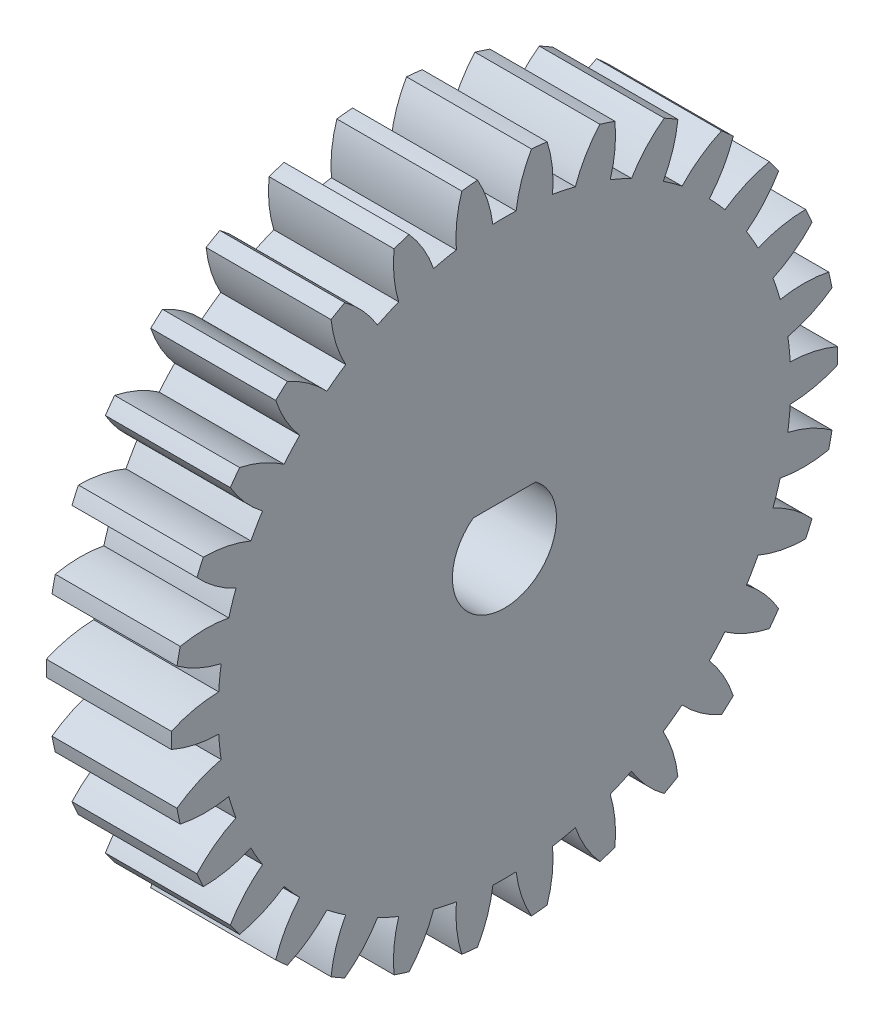
SolidWorks part; units mm, degrees
material "ABS"
ref_plane "Plane1" through (0, 0, 0) normal (0, 0, 1) x (1, 0, 0)
ref_plane "Plane2" through (0, 0, 0) normal (0, 1, 0) x (1, 0, 0)
ref_plane "Plane3" through (0, 0, 0) normal (1, 0, 0) x (0, 0, -1)
other "Configuration Table"
sketch "HoldingSke" plane through (0, 0, 0) normal (0, 1, 0) x (1, 0, 0)
  line L0 (0, 0) -> (0.866, -0.5)
  line L1 (-15, 0) -> (100, 0) construction
  line L2 (0, 0) -> (-2.1039, 2.3779)
  line L3 (0, 0) -> (-11.863, 4.5341)
  line L4 (0, 0) -> (7.479, 4.318)
  line L5 (0, 0) -> (-46.8476, -17.4728)
  line L6 (0, 0) -> (-4.9738, -3.3558)
  line L7 (-2.1039, 2.3779) -> (8.6586, 51.2059)
  line L8 (-76.2, 54.61) -> (-72.9, 54.61)
  line L9 (-67.7845, 28.3722) -> (-49.3413, 33.142)
  line L10 (-76.2, 71.12) -> (104.1128, 71.12)
  line L11 (0, 0) -> (-6, 0)
  line L12 (-76.2, 101.6) -> (-76.162, 101.6)
  line L13 (24.9733, 27.94) -> (52.9518, 28.4284)
  line L14 (24.9733, 27.94) -> (24.9743, 27.94)
  line L15 (24.9733, 27.94) -> (100.4006, 29.5858)
  line L16 (-63.627, -1) -> (-12.827, -1)
  circle A0 centre (0, 0) radius 13
  circle A1 centre (0, 0) radius 13.749
  circle A2 centre (0, 0) radius 37.5
  circle A3 centre (0, 0) radius 13
  dimension "MHD" = 27.498
  dimension "Hub_dia" = 75
  dimension "Bore" = 26
  dimension "MBD" = 26
  dimension "Num_teeth" = 30
  dimension "Pitch" = 1
  dimension "Overall_len" = 50
  dimension "Show_teeth" = 30
  dimension "Thickness" = 6
  dimension "OAL" = 50.0001
  dimension "T_dim" = 3.3
  dimension "Ap" = 14.5
  dimension "H" = 19.05
  dimension "Pitch_radius" = 180.3128
  dimension "Width" = 6
  dimension "Backlash" = 0.038
  dimension "Addendum_fac" = 1
  dimension "Dedendum_fac" = 1.25
  dimension "Clearance_fac" = 0.25
  dimension "Dedendum_add" = 0.001
  dimension "Module" = 1
sketch "BasProSke" plane through (0, 0, 0) normal (0, 1, 0) x (1, 0, 0)
  line L0 (-10, 0) -> (60, 0) construction
  line L1 (0, 0) -> (0, 16)
  line L2 (0, 0) -> (6, 0)
  line L3 (6, 0) -> (6, 16)
  line L4 (6, 16) -> (0, 16)
  dimension "Thickness" = 6
  dimension "Diameter" = 32
revolve "Base-Revolve" add sketch "BasProSke" angle 360 about L0
sketch "TooCutSke" plane through (0, 0, 0) normal (1, 0, 0) x (0, 0, -1)
  line L1 (0, 0) -> (0, 107) construction
  line L2 (0, 0) -> (-0.8515, 14.9758) construction
  line L3 (0, 0) -> (-3.1323, 29.8014) construction
  line L4 (-0.8515, 14.9758) -> (-1.5661, 14.9007) construction
  arc A0 (0.5582, 13.7377) -> (-0.5582, 13.7377) centre (0, 0) ccw
  arc A1 (1.3088, 15.9719) -> (-1.3088, 15.9719) centre (0, 0) ccw
  circle A2 centre (0, 0) radius 15 construction
  circle A3 centre (0, 0) radius 14.5222 construction
  arc A4 (-0.5582, 13.7377) -> (-1.3088, 15.9719) centre (-6.5103, 12.9812) ccw
  arc A5 (1.3088, 15.9719) -> (0.5582, 13.7377) centre (6.5103, 12.9812) ccw
  dimension "Root_dia" = 27.498
  dimension "Overcut_dia" = 32.0508
  dimension "Pitch_dia" = 30
  dimension "Base_dia" = 29.0444
  dimension "Flank_rad" = 6
  dimension "Half_ang" = 6
  dimension "Half_CT" = 0.7185
extrude "ToothCut" cut sketch "TooCutSke" along normal through all
fillet "Breaks" [suppressed] radius 0.02
fillet "RootFillets" [suppressed] radius 0.251
pattern_circular "TeethCuts" count 30 every 12 about axis through (-10, 0, 0) along (1, 0, 0) of "ToothCut", "RootFillets", "Breaks"
sketch "HubNeaOneSke" plane through (0, 0, 0) normal (-1, 0, 0) x (0, 0, 1)
  circle A0 centre (0, 0) radius 13.749
  dimension "Diameter" = 27.498
extrude "HubNearOne" [suppressed] add sketch "HubNeaOneSke" along normal blind 44.0001
sketch "HubNeaBotSke" plane through (0, 0, 0) normal (-1, 0, 0) x (0, 0, 1)
  circle A0 centre (0, 0) radius 13.749
  dimension "Diameter" = 27.498
extrude "HubNearBoth" [suppressed] add sketch "HubNeaBotSke" along normal blind 22
ref_plane "FarPln" through (6, 0, 0) normal (1, 0, 0) x (0, 0, -1)
sketch "HubFarSke" plane through (6, 0, 0) normal (1, 0, 0) x (0, 0, -1)
  circle A0 centre (0, 0) radius 13.749
  dimension "Diameter" = 27.498
extrude "HubFar" [suppressed] add sketch "HubFarSke" along normal blind 22
sketch "BorSke" plane through (0, 0, 0) normal (1, 0, 0) x (0, 0, -1)
  circle A0 centre (0, 0) radius 2.5
  dimension "Diameter" = 5
extrude "Bore" cut sketch "BorSke" along normal mid plane 100.0001
sketch "KeySke" plane through (0, 0, 0) normal (1, 0, 0) x (0, 0, -1)
  line L0 (-4, 0) -> (-4, 16.3)
  line L1 (-4, 16.3) -> (4, 16.3)
  line L2 (4, 16.3) -> (4, 0)
  line L3 (0, 0) -> (0, 34) construction
  line L4 (-4, 0) -> (4, 0)
  dimension "Offset" = 16.3
  dimension "Width" = 8
extrude "Keyway" [suppressed] cut sketch "KeySke" along normal mid plane 100.0001
pattern_circular "Keyway2" [suppressed] count 2 every 90 about axis through (-10, 0, 0) along (1, 0, 0)
sketch "Sketch1" plane through (6, 0, 0) normal (1, 0, 0) x (0, 0, -1)
  line L0 (-1.5, 2) -> (1.5, 2)
  circle A0 centre (0, 0) radius 2.5 construction
  arc A1 (1.5, 2) -> (-1.5, 2) centre (0, 0) ccw
  dimension "D1" = 3
extrude "Boss-Extrude1" add sketch "Sketch1" against normal up to surface (6 mm away) up to face at (0, 0, -2.5)
equation "' \"Module@HoldingSke\" = 6.35"
equation "' \"Num_teeth@HoldingSke\" = 12"
equation "' \"Ap@HoldingSke\" =  20"
equation "' \"Ap@HoldingSke\" = 20"
equation "' \"Width@HoldingSke\" = 0.5 * 25.4"
equation "' \"Hub_dia@HoldingSke\"= 1 * 25.4"
equation "' \"Hub_dia@HoldingSke\" = 1 * 25.4"
equation "' \"Overall_len@HoldingSke\" = 1.0 * 25.4"
equation "' \"Bore@HoldingSke\" = 0.75 * 25.4"
equation "' \"T_dim@HoldingSke\" = 0.1 * 25.4"
equation "' \"Width@KeySke\" = 0.25 * 25.4"
equation "' \"Show_teeth@HoldingSke\" = 13"
equation "' \"Backlash@HoldingSke\" = 0.009 * 25.4"
equation "' \"Addendum_fac@HoldingSke\" = 1.0"
equation "' \"Dedendum_fac@HoldingSke\" = 1.25"
equation "' \"Dedendum_add@HoldingSke\" = 0.00005 * 25.4"
equation "' \"Clearance_fac@HoldingSke\" = 0.25"
equation "\"Pitch@HoldingSke\" = 1 / \"Module@HoldingSke\""
equation "\"Overcut_dia@TooCutSke\" = (\"Num_teeth@HoldingSke\" + 2 * \"Addendum_fac@HoldingSke\") / \"Pitch@HoldingSke\" + 0.002 * 25.4"
equation "\"Pitch_dia@TooCutSke\" = \"Num_teeth@HoldingSke\" / \"Pitch@HoldingSke\""
equation "\"Base_dia@TooCutSke\" = \"Num_teeth@HoldingSke\" / \"Pitch@HoldingSke\" * cos((\"Ap@HoldingSke\"  * 3.14159265 / 180))"
equation "\"Root_dia@TooCutSke\" = (\"Num_teeth@HoldingSke\" + 2) / \"Pitch@HoldingSke\" - 2 * (\"Addendum_fac@HoldingSke\" + \"Dedendum_fac@HoldingSke\") / \"Pitch@HoldingSke\" - \"Dedendum_add@HoldingSke\" * 2"
equation "\"Half_ang@TooCutSke\" = 180 / \"Num_teeth@HoldingSke\""
equation "\"Half_CT@TooCutSke\" = \"Num_teeth@HoldingSke\" / \"Pitch@HoldingSke\" * sin((3.14159265 / 2 / \"Num_teeth@HoldingSke\")) / 2 - 7 * \"Backlash@HoldingSke\" / 4"
equation "\"Flank_rad@TooCutSke\" = \"Num_teeth@HoldingSke\" / \"Pitch@HoldingSke\" / 5"
equation "\"Radius@RootFillets\" = \"Clearance_fac@HoldingSke\" / \"Pitch@HoldingSke\" + \"Dedendum_add@HoldingSke\""
equation "\"Break_rad@Breaks\" = 0.02 / \"Pitch@HoldingSke\""
equation "\"Thickness@HoldingSke\" = \"Width@HoldingSke\""
equation "\"OAL@HoldingSke\" = \"Thickness@HoldingSke\""
equation "\"MHD@HoldingSke\" = (\"Num_teeth@HoldingSke\" + 2) / \"Pitch@HoldingSke\" - 2 * (\"Addendum_fac@HoldingSke\" + \"Dedendum_fac@HoldingSke\")  / \"Pitch@HoldingSke\" - \"Dedendum_add@HoldingSke\" * 2"
equation "\"MBD@HoldingSke\" = (\"Num_teeth@HoldingSke\" + 2) / \"Pitch@HoldingSke\" - 2 * (\"Addendum_fac@HoldingSke\" + \"Dedendum_fac@HoldingSke\")  / \"Pitch@HoldingSke\" - \"Dedendum_add@HoldingSke\" * 2 - 0.002 * 25.4"
equation "\"MHD@HoldingSke\" = ((sgn( \"MHD@HoldingSke\" - \"Hub_dia@HoldingSke\" )-1)*( \"MHD@HoldingSke\" - \"Hub_dia@HoldingSke\" ))/-2+ \"Hub_dia@HoldingSke\""
equation "\"MBD@HoldingSke\" = ((sgn( \"MBD@HoldingSke\" - \"Bore@HoldingSke\" )-1)*( \"MBD@HoldingSke\" - \"Bore@HoldingSke\" ))/-2+ \"Bore@HoldingSke\""
equation "\"OAL@HoldingSke\" = ((sgn( \"OAL@HoldingSke\" - \"Overall_len@HoldingSke\" )+1)*( \"OAL@HoldingSke\" - \"Overall_len@HoldingSke\" ))/2 + \"Overall_len@HoldingSke\" + 0.000002 * 25.4"
equation "\"Num_teeth@TeethCuts\" = int( \"Show_teeth@HoldingSke\" ) + 1"
equation "\"Num_teeth@TeethCuts\" = ((sgn( \"Num_teeth@TeethCuts\" - \"Num_teeth@HoldingSke\" )-1)*( \"Num_teeth@TeethCuts\" - \"Num_teeth@HoldingSke\" ))/-2+ \"Num_teeth@HoldingSke\""
equation "\"Num_teeth@TeethCuts\" = ((sgn( \"Num_teeth@TeethCuts\" - 2.0)+1)*( \"Num_teeth@TeethCuts\" - 2.0))/2 +2.0"
equation "\"Angle@TeethCuts\" = 360.0 / \"Num_teeth@HoldingSke\""
equation "\"Diameter@BasProSke\" = (\"Num_teeth@HoldingSke\" + 2 * \"Addendum_fac@HoldingSke\") / \"Pitch@HoldingSke\""
equation "\"Thickness@BasProSke\"  = \"Thickness@HoldingSke\""
equation "' \"Fillet_rad@BasProSke\" =  \"Thickness@HoldingSke\" * 0.05"
equation "' \"Fillet_rad@BasProSke\" = \"Thickness@HoldingSke\" * 0.05"
equation "\"MHD@HoldingSke\" = ((sgn( \"MHD@HoldingSke\" - \"Root_dia@TooCutSke\" )-1)*( \"MHD@HoldingSke\" - \"Root_dia@TooCutSke\" ))/-2+ \"Root_dia@TooCutSke\""
equation "\"Diameter@HubNeaOneSke\" = \"MHD@HoldingSke\""
equation "\"Length@HubNearOne\" = \"OAL@HoldingSke\" - \"Thickness@BasProSke\""
equation "\"Diameter@HubNeaBotSke\" = \"MHD@HoldingSke\""
equation "\"Length@HubNearBoth\" = ( \"OAL@HoldingSke\" - \"Thickness@BasProSke\" ) / 2.0"
equation "\"Thickness@FarPln\" = \"Thickness@BasProSke\""
equation "\"Diameter@HubFarSke\" = \"MHD@HoldingSke\""
equation "\"Length@HubFar\" = ( \"OAL@HoldingSke\" - \"Thickness@BasProSke\" ) / 2.0"
equation "\"D1@Bore\" = \"OAL@HoldingSke\" * 2.0"
equation "\"D1@Keyway\" = \"OAL@HoldingSke\" * 2.0"
equation "\"Offset@KeySke\" = \"T_dim@HoldingSke\" + \"MBD@HoldingSke\" / 2.0"
